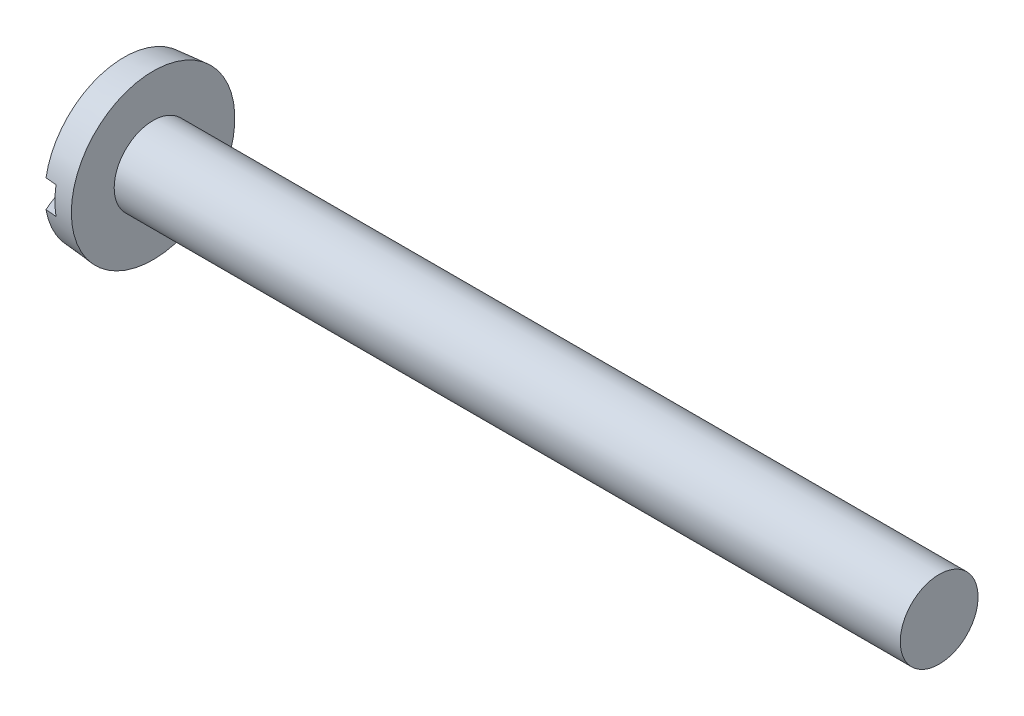
SolidWorks part; units mm, degrees
ref_plane "Plane1" through (0, 0, 0) normal (0, 0, 1) x (1, 0, 0)
ref_plane "Plane2" through (0, 0, 0) normal (0, 1, 0) x (1, 0, 0)
ref_plane "Plane3" through (0, 0, 0) normal (1, 0, 0) x (0, 0, -1)
sketch "BodySke" plane through (0, 0, 0) normal (0, 0, 1) x (1, 0, 0)
  line L0 (1.4986, 1.2573) -> (1.4986, 2.6416)
  line L1 (1.4986, 2.6416) -> (0.5588, 2.5594)
  line L2 (-25.4, 0) -> (127, 0) construction
  line L3 (1.4986, -2.6416) -> (0.5588, -2.5594) construction
  line L4 (1.4986, 1.2573) -> (26.8986, 1.2573)
  line L5 (26.8986, 1.2573) -> (26.8986, 0)
  line L6 (26.8986, 0) -> (0, 0)
  line L7 (1.4986, -1.2573) -> (26.8986, -1.2573) construction
  line L8 (1.9533, 6.35) -> (1.9533, -3.175) construction
  line L9 (1.4986, 6.35) -> (1.4986, -3.175) construction
  arc A0 (0, 0) -> (0.5588, 2.5594) centre (6.1405, 0) cw
  dimension "Head_ang" = 85
revolve "Base-Revolve" add sketch "BodySke" angle 360 about L2
cosmetic thread "ThreadCosmetic" [suppressed] parameters "Thread_length"=24.9453, "Thread_minor"=1.9761
sketch "Sketch2" plane through (0, 0, 0) normal (1, 0, 0) x (0, 0, -1)
  line L0 (2.6416, -0.4445) -> (2.6416, 0.4445)
  line L1 (2.6416, 0.4445) -> (-2.6416, 0.4445)
  line L2 (-2.6416, 0.4445) -> (-2.6416, -0.4445)
  line L3 (-2.6416, -0.4445) -> (2.6416, -0.4445)
extrude "Slot" cut sketch "Sketch2" along normal blind 0.9144
sketch "Sketch3" plane through (0, 0, 0) normal (1, 0, 0) x (0, 0, -1)
  line L0 (-0.3937, 1.7272) -> (0.3937, 1.7272)
  line L1 (0.3937, 1.7272) -> (0.3937, -1.7272)
  line L2 (0.3937, -1.7272) -> (-0.3937, -1.7272)
  line L3 (-0.3937, -1.7272) -> (-0.3937, 1.7272)
ref_plane "Plane4" through (1.9558, 0, 0) normal (1, 0, 0) x (0, 0, -1)
sketch "Sketch4" plane through (1.9558, 0, 0) normal (1, 0, 0) x (0, 0, -1)
  line L0 (-0.1968, 0.1968) -> (0.1968, 0.1968)
  line L1 (0.1968, 0.1968) -> (0.1969, -0.1968)
  line L2 (0.1969, -0.1968) -> (-0.1968, -0.1969)
  line L3 (-0.1968, -0.1969) -> (-0.1968, 0.1968)
loft "Cross" [suppressed] cut profiles "Sketch3", "Sketch4"
pattern_circular "CirPattern1" [suppressed] count 2 every 90 about axis through (-25.4, 0, 0) along (1, 0, 0)
sketch "ThdSchSke" plane through (0, 0, 0) normal (0, 0, 1) x (1, 0, 0)
  line L0 (1.9533, -0.9881) -> (1.7647, -1.2573)
  line L1 (1.9533, -0.9881) -> (2.1418, -1.2573)
  line L2 (2.1418, -1.2573) -> (2.1418, -1.5716)
  line L3 (-3.175, 0) -> (5.1513, 0) construction
  line L5 (2.1418, -1.5716) -> (1.7647, -1.5716)
  line L6 (1.7647, -1.5716) -> (1.7647, -1.2573)
  dimension "SideAngle" = 55
  dimension "VeeAngle" = 70
revolve "ThreadSchematic" [suppressed] cut sketch "ThdSchSke" angle 360 about L3
pattern_linear "ThdSchPat" [suppressed]
equation "\"D1@Sketch3\" = \"Cross_width@Sketch3\" / 2"
equation "\"D2@Sketch3\" = \"Cross_dia@Sketch3\" / 2"
equation "\"D1@Sketch4\" = \"Cross_width@Sketch3\"*.5"
equation "\"D2@Sketch4\" = \"D1@Sketch4\" / 2"
equation "\"D3@Sketch4\" = \"D1@Sketch4\""
equation "\"D4@Sketch4\" = \"D2@Sketch4\""
equation "\"D1@Sketch2\" = \"Head_dia@BodySke\""
equation "\"D2@Sketch2\" = \"D1@Sketch2\" / 2"
equation "\"D3@Sketch2\" = \"Slot_width@Sketch2\" / 2"
equation "\"Thread_length@ThreadCosmetic\" = ((sgn( (\"Length@BodySke\" - \"Advance@BodySke\" ) - \"Thread_nom@BodySke\" )-1)*( (\"Length@BodySke\" - \"Advance@BodySke\" ) - \"Thread_nom@BodySke\" ))/-2+ \"Thread_nom@BodySke\""
equation "\"Thread_minor@ThdSchSke\" = \"Thread_minor@ThreadCosmetic\""
equation "\"Diameter@ThdSchSke\" = \"Diameter@BodySke\""
equation "\"Overcut@ThdSchSke\" = \"Diameter@BodySke\" * 1.25"
equation "\"Start@ThdSchSke\" = \"Head_ht@BodySke\" + \"Length@BodySke\" - \"Thread_length@ThreadCosmetic\"  '---Non-countersunk---"
equation "\"Num_threads@ThdSchPat\" = int( \"Thread_length@ThreadCosmetic\" / \"Advance@BodySke\" + 0.999 )  + 1"
equation "\"Advance@ThdSchPat\" = \"Thread_length@ThreadCosmetic\" /  (\"Num_threads@ThdSchPat\" - 1) 'relax it"
